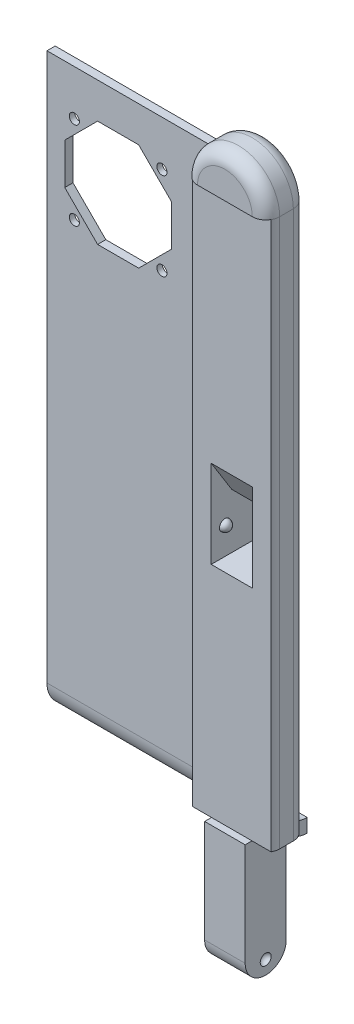
SolidWorks part; units mm, degrees
ref_plane "Front Plane" through (0, 0, 0) normal (0, 0, 1) x (1, 0, 0)
ref_plane "Top Plane" through (0, 0, 0) normal (0, 1, 0) x (1, 0, 0)
ref_plane "Right Plane" through (0, 0, 0) normal (1, 0, 0) x (0, 0, -1)
sketch "Sketch1" plane through (0, 0, 0) normal (0, 0, 1) x (1, 0, 0)
  line L0 (-15, 100) -> (-15, -100)
  line L1 (-15, -100) -> (-7.4, -100)
  line L2 (-7.4, -100) -> (-7.4, -150)
  line L3 (-7.4, -150) -> (7.4, -150)
  line L4 (7.4, -150) -> (7.4, -100)
  line L5 (7.4, -100) -> (15, -100)
  line L6 (15, -100) -> (15, 100)
  arc A0 (15, 100) -> (-15, 100) centre (0, 100) ccw
  dimension "D1" = 15
  dimension "D2" = 250
  dimension "D3" = 50
  dimension "D4" = 15
  dimension "D5" = 14.8
  dimension "D6" = 100
extrude "Boss-Extrude1" add sketch "Sketch1" along normal mid plane 15
fillet "Fillet1" radius 5 6 edges at (-15, 0, -7.5) (0, 115, -7.5) (-15, 0, 7.5) (0, 115, 7.5) (15, 0, -7.5) (15, 0, 7.5)
sketch "Sketch2" plane through (0, 0, 7.5) normal (0, 0, 1) x (1, 0, 0)
  line L0 (-10, 100) -> (-10, -100) construction
  line L1 (-7.5, 0) -> (7.5, 0)
  line L2 (-7.5, 0) -> (-7.5, -20)
  line L3 (-7.5, -20) -> (7.5, -20)
  line L4 (7.5, 0) -> (7.5, -20)
  dimension "D1" = 20
  dimension "D2" = 15
  dimension "D3" = 2.5
extrude "Cut-Extrude1" cut sketch "Sketch2" against normal through all
sketch "Sketch5" plane through (0, 0, 0) normal (0, 0, 1) x (1, 0, 0)
  line L0 (-35.5803, -140) -> (47.5468, -140) construction
  line L1 (-10, -100) -> (-7.4, -100) construction
  line L2 (-7.4, -140) -> (-5.4, -140)
  line L3 (-7.4, -100) -> (-7.4, -150) construction
  line L4 (-7.4, -138) -> (-7.4, -140)
  line L5 (7.4, -140) -> (5.4, -140)
  line L6 (7.4, -150) -> (7.4, -100) construction
  line L7 (7.4, -138) -> (7.4, -140)
  arc A0 (-5.4, -140) -> (-7.4, -138) centre (-7.4, -140) ccw
  arc A1 (5.4, -140) -> (7.4, -138) centre (7.4, -140) cw
  dimension "D1" = 40
  dimension "D2" = 2
  dimension "D3" = 2
revolve "Cut-Revolve1" cut sketch "Sketch5" angle 360 about L0
fillet "Fillet6" radius 5 2 edges at (-7.4, -150, 0) (7.4, -150, 0)
sketch "Sketch7" plane through (7.4, 0, 0) normal (1, 0, 0) x (0, 0, -1)
  line L0 (-7.5, -145) -> (-7.5, -100) construction
  line L1 (7.5, -145) -> (7.5, -100) construction
  line L2 (-7.5, -145) -> (7.5, -145) construction
  line L3 (-7.5, -137.5) -> (-7.5, -150)
  line L4 (-7.5, -150) -> (7.5, -150)
  line L5 (7.5, -150) -> (7.5, -137.5)
  arc A0 (-7.5, -137.5) -> (7.5, -137.5) centre (0, -137.5) ccw
extrude "Cut-Extrude2" cut sketch "Sketch7" against normal through all
sketch "Sketch9" plane through (0, 0, 0) normal (0, 0, 1) x (1, 0, 0)
  line L0 (-32.2513, -10) -> (37.8356, -10) construction
  line L1 (7.5, 0) -> (-7.5, 0) construction
  line L2 (-7.5, -10) -> (-5.5, -10)
  line L3 (-7.5, 0) -> (-7.5, -20) construction
  line L4 (-7.5, -8) -> (-7.5, -10)
  line L5 (7.5, -10) -> (5.5, -10)
  line L6 (7.5, -20) -> (7.5, 0) construction
  line L7 (7.5, -8) -> (7.5, -10)
  arc A0 (-5.5, -10) -> (-7.5, -8) centre (-7.5, -10) ccw
  arc A1 (5.5, -10) -> (7.5, -8) centre (7.5, -10) cw
  dimension "D1" = 10
  dimension "D2" = 2
  dimension "D3" = 2
revolve "Revolve2" add sketch "Sketch9" angle 360 about L0
sketch "Sketch10" plane through (0, 0, 0) normal (1, 0, 0) x (0, 0, -1)
  line L0 (7.5, -100) -> (7.5, 100)
  line L1 (7.5, 100) -> (10.5, 100)
  line L2 (10.5, 100) -> (10.5, -98.5193)
  line L3 (17.5, -105) -> (17.5, -110)
  arc A0 (10.5, -98.5193) -> (17.5, -105) centre (17, -98.5193) ccw
  arc A1 (17.5, -110) -> (7.5, -100) centre (17.5, -100) cw
  dimension "D2" = 10
  dimension "D4" = 6.5
  dimension "D1" = 5
  dimension "D3" = 3
  dimension "D5" = 10
extrude "Boss-Extrude2" add sketch "Sketch10" against normal blind 80
sketch "Sketch11" plane through (0, 0, 0) normal (1, 0, 0) x (0, 0, -1)
  line L0 (17.5, -110) -> (17.5, -105) construction
  line L1 (7.5, 100) -> (7.5, -100) construction
  line L2 (10.5, 100) -> (7.5, 100) construction
  line L3 (10.5, -98.5193) -> (10.5, 100) construction
  line L4 (17.5, -110) -> (17.5, -105)
  line L5 (7.5, 100) -> (7.5, -100)
  line L6 (10.5, 100) -> (7.5, 100)
  line L7 (10.5, -98.5193) -> (10.5, 100)
  arc A0 (10.5, -98.5193) -> (17.5, -105) centre (17, -98.5193) ccw construction
  arc A1 (7.5, -100) -> (17.5, -110) centre (17.5, -100) ccw construction
  arc A2 (10.5, -98.5193) -> (17.5, -105) centre (17, -98.5193) ccw
  arc A3 (7.5, -100) -> (17.5, -110) centre (17.5, -100) ccw
extrude "Boss-Extrude3" add sketch "Sketch11" along normal blind 5
sketch "Sketch12" plane through (0, 0, -10.5) normal (0, 0, -1) x (-1, 0, 0)
  line L0 (7.5, -20) -> (-5, -20) construction
  line L1 (7.5, -20) -> (-5, -20)
  line L2 (7.5, 0) -> (7.5, -20) construction
  line L3 (7.5, 0) -> (-5, 0) construction
  line L4 (80, 100) -> (-5, 100)
  line L5 (-5, 100) -> (-5, -98.5193)
  line L6 (-5, -98.5193) -> (80, -98.5193)
  line L7 (80, -98.5193) -> (80, 100)
  line L9 (-5, 0) -> (-5, -20)
  line L12 (7.5, 0) -> (7.5, -20)
  line L13 (7.5, 0) -> (-5, 0)
  dimension "D1" = 0
extrude "Cut-Extrude3" cut sketch "Sketch12" against normal blind 3
sketch "Sketch13" plane through (-15, 0, 0) normal (-1, 0, 0) x (0, 0, 1)
  line L0 (7.5, -100) -> (5, -100)
  line L1 (2.5, -100) -> (7.5, -100) construction
  line L2 (5, -100) -> (5, 100)
  line L3 (7.5, 100) -> (2.5, 100) construction
  line L4 (5, 100) -> (7.5, 100)
  line L5 (7.5, 100) -> (7.5, -100) construction
  line L6 (7.5, 100) -> (7.5, -100)
extrude "Cut-Extrude4" cut sketch "Sketch13" against normal through all
sketch "Sketch14" plane through (0, 0, -10.5) normal (0, 0, -1) x (-1, 0, 0)
  line L0 (80, -98.5193) -> (-5, -98.5193) construction
  line L1 (80, -98.5193) -> (80, 100) construction
  line L2 (61.5, 86.9807) -> (46.5, 86.9807)
  line L3 (46.5, 86.9807) -> (34.5, 74.9807)
  line L4 (34.5, 74.9807) -> (34.5, 59.9807)
  line L5 (34.5, 59.9807) -> (46.5, 47.9807)
  line L6 (46.5, 47.9807) -> (61.5, 47.9807)
  line L7 (61.5, 47.9807) -> (73.5, 59.9807)
  line L8 (73.5, 59.9807) -> (73.5, 74.9807)
  line L9 (73.5, 74.9807) -> (61.5, 86.9807)
  circle A0 centre (70, 51.4807) radius 1.85
  circle A1 centre (70, 83.4807) radius 1.85
  circle A2 centre (38, 83.4807) radius 1.85
  circle A3 centre (38, 51.4807) radius 1.85
  point P8 (54, 86.9807)
  point P21 (34.5, 67.4807)
  dimension "D4" = 3.7
  dimension "D1" = 150
  dimension "D2" = 32
  dimension "D3" = 32
  dimension "D5" = 10
  dimension "D6" = 15
  dimension "D7" = 16
  dimension "D8" = 16
  dimension "D9" = 39
extrude "Cut-Extrude5" cut sketch "Sketch14" against normal blind 10
sketch "Sketch15" plane through (0, 0, -10.5) normal (0, 0, -1) x (-1, 0, 0)
  circle A0 centre (70, 83.4807) radius 3.25
  circle A1 centre (38, 83.4807) radius 3.25
  circle A2 centre (38, 51.4807) radius 3.25
  circle A3 centre (70, 51.4807) radius 3.25
  dimension "D1" = 6.5
extrude "Cut-Extrude6" cut sketch "Sketch15" against normal blind 1
sketch "Sketch16" plane through (0, 0, 0) normal (1, 0, 0) x (0, 0, -1)
  line L0 (2.5, 0) -> (-5, 12)
  line L1 (2.5, 100) -> (2.5, -100) construction
  line L2 (-5, 100) -> (-5, -100) construction
  line L3 (-5, 12) -> (-5, 0)
  line L4 (-5, 0) -> (2.5, 0)
  dimension "D1" = 12
extrude "Cut-Extrude7" cut sketch "Sketch16" against normal mid plane 15
